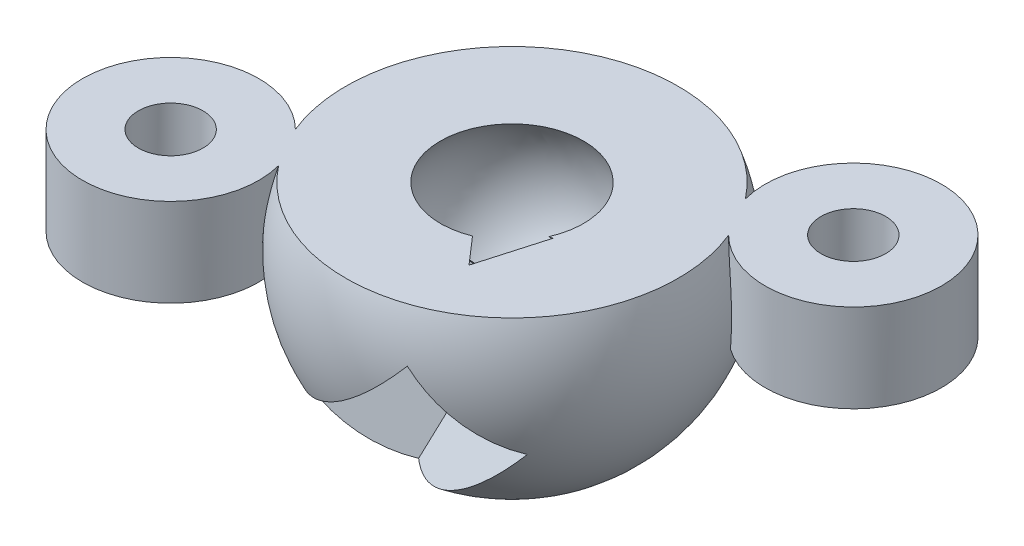
SolidWorks part; units mm, degrees
other "Compression Link 3 Fixed Ball Retainer"
ref_plane "Front Plane" through (0, 0, 0) normal (0, 0, 1) x (1, 0, 0)
ref_plane "Top Plane" through (0, 0, 0) normal (0, 1, 0) x (1, 0, 0)
ref_plane "Right Plane" through (0, 0, 0) normal (1, 0, 0) x (0, 0, -1)
sketch3d "Retainer Dome axis line"
  line L0 (-71.2917, -83, -25.9808) -> (-71.2917, -63, -25.9808) construction
ref_axis "Retainer Dome axis" through (-71.2917, -83, -25.9808) along (0, 1, 0)
sketch3d "Retainer Dome Section Sketch datum points"
  point P0 (-71.2917, -73, -25.9808)
  point P1 (-76.2917, -73, -34.641)
  point P2 (-71.2917, -63, -25.9808)
ref_plane "Retainer Dome Section Sketch plane" through (-42.2187, 0, 24.375) normal (0.866, 0, -0.5) x (-0.5, 0, -0.866)
sketch "Retainer Dome Section Sketch" plane through (-42.2187, 0, 24.375) normal (0.866, 0, -0.5) x (-0.5, 0, -0.866)
  line L0 (63.8027, -71) -> (58.1458, -71)
  line L1 (58.1458, -71) -> (58.1458, -79)
  arc A0 (58.1458, -79) -> (63.8027, -71) centre (58.1458, -73) ccw
revolve "Retainer Dome" add sketch "Retainer Dome Section Sketch" angle 360 about axis through (-71.2917, -83, -25.9808) along (0, 1, 0)
sketch3d "Retainer Feature 3 profile datum points"
  point P0 (-78.6529, -71, -21.7308)
  point P1 (-68.6529, -71, -21.7308)
  point P2 (-78.6529, -71, -11.7308)
ref_plane "Retainer Feature 3 profile plane" through (0, -71, 0) normal (0, -1, 0) x (-1, 0, 0)
sketch "Retainer Feature 3 profile" plane through (0, -71, 0) normal (0, -1, 0) x (-1, 0, 0)
  circle A0 centre (78.6529, 21.7308) radius 3
extrude "Retainer Feature 3" add sketch "Retainer Feature 3 profile" along normal blind 3
sketch3d "Retainer Feature 4 profile datum points"
  point P0 (-63.9304, -71, -30.2308)
  point P1 (-53.9304, -71, -30.2308)
  point P2 (-63.9304, -71, -20.2308)
ref_plane "Retainer Feature 4 profile plane" through (0, -71, 0) normal (0, -1, 0) x (-1, 0, 0)
sketch "Retainer Feature 4 profile" plane through (0, -71, 0) normal (0, -1, 0) x (-1, 0, 0)
  circle A0 centre (63.9304, 30.2308) radius 3
extrude "Retainer Feature 4" add sketch "Retainer Feature 4 profile" along normal blind 3
sketch3d "Spherical Seat axis line"
  line L0 (-79.9519, -73, -20.9808) -> (-62.6314, -73, -30.9808) construction
ref_axis "Spherical Seat axis" through (-79.9519, -73, -20.9808) along (0.866, 0, -0.5)
sketch3d "Spherical Seat Sketch datum points"
  point P0 (-71.2917, -73, -25.9808)
  point P1 (-76.2917, -73, -34.641)
  point P2 (-62.6314, -73, -30.9808)
ref_plane "Spherical Seat Sketch plane" through (0, -73, 0) normal (0, -1, 0) x (-1, 0, 0)
sketch "Spherical Seat Sketch" plane through (0, -73, 0) normal (0, -1, 0) x (-1, 0, 0)
  line L0 (68.5637, 27.5558) -> (74.0196, 24.4058)
  arc A0 (74.0196, 24.4058) -> (68.5637, 27.5558) centre (71.2917, 25.9808) ccw
revolve "Spherical Seat" cut sketch "Spherical Seat Sketch" angle 360 about axis through (-79.9519, -73, -20.9808) along (0.866, 0, -0.5)
sketch3d "Retainer Feature 6 profile datum points"
  point P0 (-78.6529, -70, -21.7308)
  point P1 (-68.6529, -70, -21.7308)
  point P2 (-78.6529, -70, -11.7308)
ref_plane "Retainer Feature 6 profile plane" through (0, -70, 0) normal (0, -1, 0) x (-1, 0, 0)
sketch "Retainer Feature 6 profile" plane through (0, -70, 0) normal (0, -1, 0) x (-1, 0, 0)
  circle A0 centre (78.6529, 21.7308) radius 1.1
extrude "Retainer Feature 6" cut sketch "Retainer Feature 6 profile" along normal blind 4.25
sketch3d "Retainer Feature 7 profile datum points"
  point P0 (-78.6529, -72.8, -21.7308)
  point P1 (-68.6529, -72.8, -21.7308)
  point P2 (-78.6529, -72.8, -11.7308)
ref_plane "Retainer Feature 7 profile plane" through (0, -72.8, 0) normal (0, -1, 0) x (-1, 0, 0)
sketch "Retainer Feature 7 profile" plane through (0, -72.8, 0) normal (0, -1, 0) x (-1, 0, 0)
  circle A0 centre (78.6529, 21.7308) radius 2.1
extrude "Retainer Feature 7" cut sketch "Retainer Feature 7 profile" along normal blind 1.45
sketch3d "Retainer Feature 8 profile datum points"
  point P0 (-63.9304, -70, -30.2308)
  point P1 (-53.9304, -70, -30.2308)
  point P2 (-63.9304, -70, -20.2308)
ref_plane "Retainer Feature 8 profile plane" through (0, -70, 0) normal (0, -1, 0) x (-1, 0, 0)
sketch "Retainer Feature 8 profile" plane through (0, -70, 0) normal (0, -1, 0) x (-1, 0, 0)
  circle A0 centre (63.9304, 30.2308) radius 1.1
extrude "Retainer Feature 8" cut sketch "Retainer Feature 8 profile" along normal blind 4.25
sketch3d "Retainer Feature 9 profile datum points"
  point P0 (-63.9304, -72.8, -30.2308)
  point P1 (-53.9304, -72.8, -30.2308)
  point P2 (-63.9304, -72.8, -20.2308)
ref_plane "Retainer Feature 9 profile plane" through (0, -72.8, 0) normal (0, -1, 0) x (-1, 0, 0)
sketch "Retainer Feature 9 profile" plane through (0, -72.8, 0) normal (0, -1, 0) x (-1, 0, 0)
  circle A0 centre (63.9304, 30.2308) radius 2.1
extrude "Retainer Feature 9" cut sketch "Retainer Feature 9 profile" along normal blind 1.45
sketch3d "Middle Right Fixed Compression Ball Retainer 1 Angular Clearance Sketch 21 datum points"
  point P0 (-71.2917, -73, -25.9808)
  point P1 (-79.3909, -78.3859, -28.3032)
  point P2 (-65.5478, -79.4818, -30.9801)
ref_plane "Middle Right Fixed Compression Ball Retainer 1 Angular Clearance Sketch 21 plane" through (1.087, -4.9285, 7.6389) normal (0.1187, -0.5383, 0.8343) x (0.9929, 0.0644, -0.0998)
sketch "Middle Right Fixed Compression Ball Retainer 1 Angular Clearance Sketch 21" plane through (1.087, -4.9285, 7.6389) normal (0.1187, -0.5383, 0.8343) x (0.9929, 0.0644, -0.0998)
  line L0 (-71.3831, -72.0252) -> (-76.6036, -75.7275)
  line L1 (-76.6036, -75.7275) -> (-74.4053, -78.8271)
  line L2 (-74.4053, -78.8271) -> (-69.1849, -75.1249)
  line L3 (-69.1849, -75.1249) -> (-71.3831, -72.0252)
extrude "Retainer Feature 12" cut sketch "Middle Right Fixed Compression Ball Retainer 1 Angular Clearance Sketch 21" along normal blind 10
